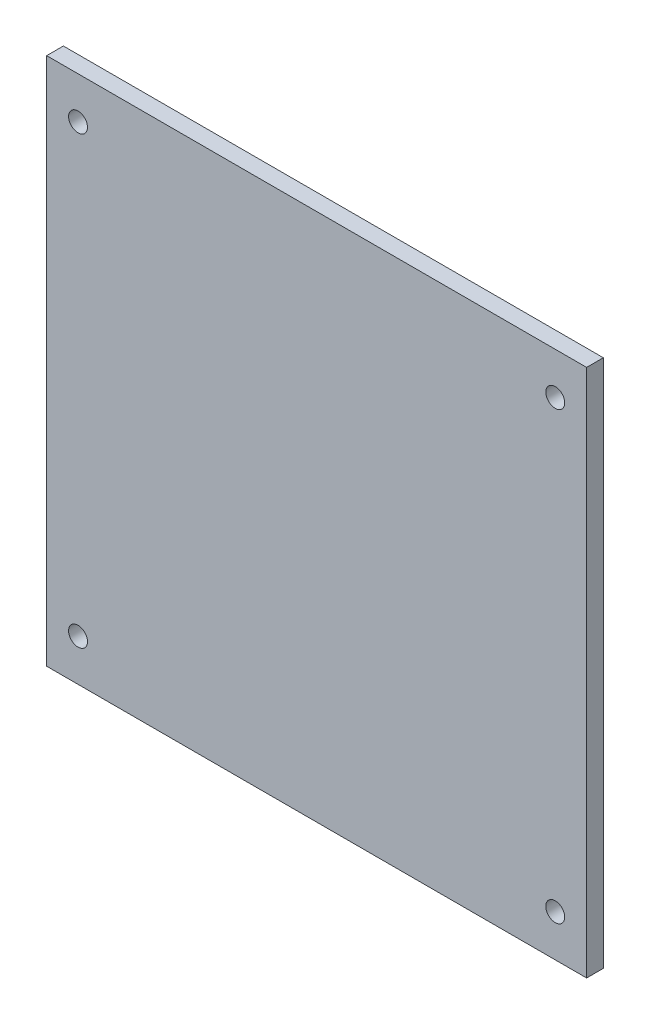
SolidWorks part; units mm, degrees
material "6061-T6 (SS)"
ref_plane "Front Plane" through (0, 0, 0) normal (0, 0, 1) x (1, 0, 0)
ref_plane "Top Plane" through (0, 0, 0) normal (0, 1, 0) x (1, 0, 0)
ref_plane "Right Plane" through (0, 0, 0) normal (1, 0, 0) x (0, 0, -1)
sketch "Body sketch" plane through (0, 0, 0) normal (0, 0, 1) x (1, 0, 0)
  line L1 (0, 0) -> (97, 0)
  line L2 (0, 0) -> (0, 95)
  line L3 (0, 95) -> (97, 95)
  line L4 (97, 0) -> (97, 95)
extrude "Body" add sketch "Body sketch" along normal blind 3
sketch "Holes sketch" plane through (0, 0, 0) normal (0, 0, 1) x (1, 0, 0)
  circle A0 centre (5.635, 7.495) radius 1.7
  circle A1 centre (91.365, 7.495) radius 1.7
  circle A2 centre (5.635, 87.505) radius 1.7
  circle A3 centre (91.365, 87.505) radius 1.7
extrude "Holes" cut sketch "Holes sketch" against normal through all and the other way through all
